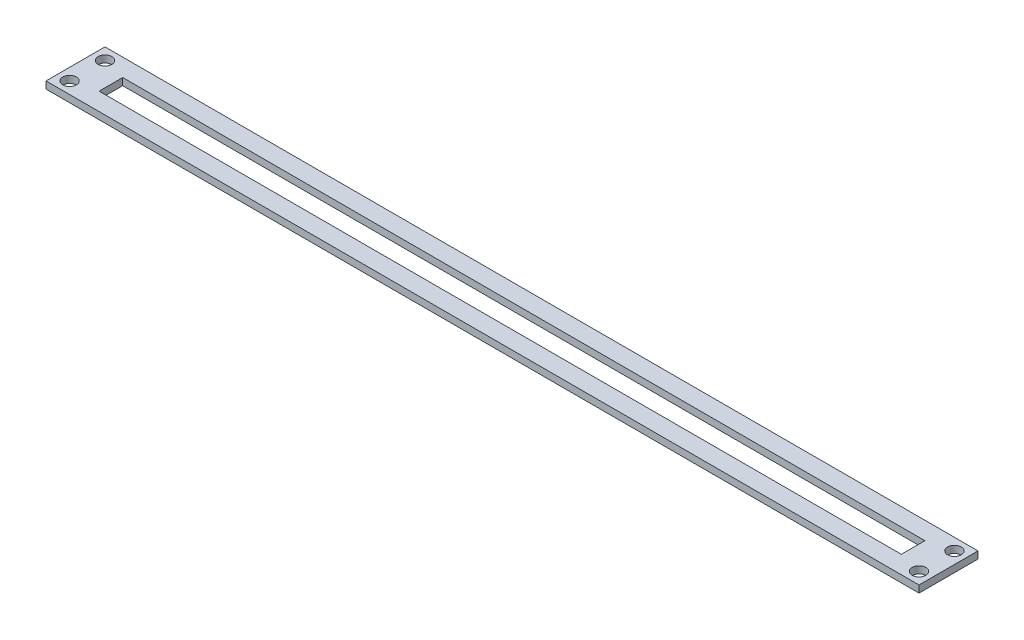
SolidWorks part; units mm, degrees
ref_plane "Plan de face" through (0, 0, 0) normal (0, 0, 1) x (1, 0, 0)
ref_plane "Plan de dessus" through (0, 0, 0) normal (0, 1, 0) x (1, 0, 0)
ref_plane "Plan de droite" through (0, 0, 0) normal (1, 0, 0) x (0, 0, -1)
sketch "Esquisse1" plane through (0, 0, 0) normal (0, 1, 0) x (1, 0, 0)
  line L1 (-185, 12.5) -> (185, 12.5)
  line L2 (-185, 12.5) -> (-185, -12.5)
  line L3 (-185, -12.5) -> (185, -12.5)
  line L4 (185, 12.5) -> (185, -12.5)
  line L5 (-185, 12.5) -> (185, -12.5) construction
  line L6 (-185, -12.5) -> (185, 12.5) construction
  line L7 (-170, 5) -> (170, 5)
  line L8 (-170, 5) -> (-170, -5)
  line L9 (-170, -5) -> (170, -5)
  line L10 (170, 5) -> (170, -5)
  line L11 (-170, 5) -> (170, -5) construction
  line L12 (-170, -5) -> (170, 5) construction
  point P0 (0, 0)
  point P6 (0, 0)
  dimension "D1" = 340
  dimension "D2" = 370
  dimension "D3" = 25
  dimension "D4" = 10
extrude "Boss.-Extru.1" add sketch "Esquisse1" along normal blind 3
hole_wizard "Dégagement M51" positions "Esquisse3" profile "Esquisse2" hole size "M5" standard "Din"
sketch "Esquisse3" plane through (0, 3, 0) normal (0, 1, 0) x (1, 0, 0)
  line L12 (180, -7.5) -> (180, 7.5)
  line L13 (180, 7.5) -> (-180, 7.5)
  line L14 (-180, 7.5) -> (-180, -7.5)
  line L15 (-180, -7.5) -> (180, -7.5)
  line L16 (180, -7.5) -> (180, 7.5)
  line L17 (180, 7.5) -> (-180, 7.5)
  line L18 (-180, 7.5) -> (-180, -7.5)
  line L19 (-180, -7.5) -> (180, -7.5)
  point P0 (-180, 7.5)
  point P2 (-180, -7.5)
  point P4 (180, -7.5)
  point P6 (180, 7.5)
  dimension "D1" = 5
sketch "Esquisse2" plane through (-180, 3, -7.5) normal (1, 0, 0) x (0, 0, 1)
  line L0 (0, 0) -> (0, 4)
  line L1 (0, 4) -> (2.9, 4)
  line L2 (2.9, 4) -> (2.9, 0)
  line L5 (2.9, 0) -> (0, 0)
  line L10 (0, 4) -> (-2.9, 4) construction
  line L11 (0, -6.35) -> (0, 107.95) construction
  dimension "Diamètre du perçage" = 5.8
  dimension "Profondeur du perçage" = 4
  dimension "Angle de pointe" = 180
